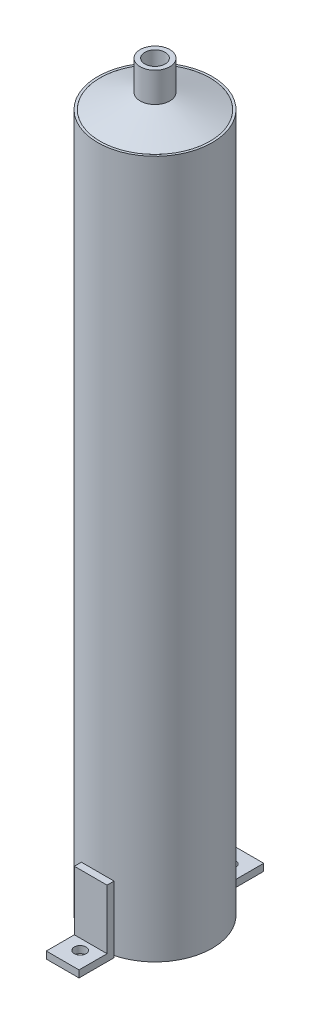
SolidWorks part; units mm, degrees
ref_plane "Front Plane" through (0, 0, 0) normal (0, 0, 1) x (1, 0, 0)
ref_plane "Top Plane" through (0, 0, 0) normal (0, 1, 0) x (1, 0, 0)
ref_plane "Right Plane" through (0, 0, 0) normal (1, 0, 0) x (0, 0, -1)
sketch "Sketch1" plane through (0, 0, 0) normal (0, 1, 0) x (1, 0, 0)
  circle A0 centre (0, 0) radius 23.5
  dimension "D1" = 47
extrude "Extrude-Thin1" add sketch "Sketch1" along normal blind 298.45 thin
ref_plane "Plane1" through (0, 304.8, 0) normal (0, 1, 0) x (1, 0, 0)
sketch "Sketch7" plane through (0, 0, 0) normal (0, -1, 0) x (1, 0, 0)
  line L0 (-27.2962, 0) -> (21.569, 0) construction
  line L1 (0, -24.5) -> (0, 25.9198) construction
  line L3 (-1.524, -21.214) -> (1.524, -21.214)
  line L4 (-1.524, -21.214) -> (-1.524, -23.5)
  line L5 (-1.524, -23.5) -> (1.524, -23.5)
  line L6 (1.524, -21.214) -> (1.524, -23.5)
  line L7 (-1.524, -21.214) -> (1.524, -23.5) construction
  line L8 (-1.524, -23.5) -> (1.524, -21.214) construction
  line L20 (-21.214, 1.524) -> (-23.5, 1.524)
  line L21 (-21.214, 1.524) -> (-21.214, -1.524)
  line L22 (-21.214, -1.524) -> (-23.5, -1.524)
  line L23 (-23.5, 1.524) -> (-23.5, -1.524)
  line L24 (1.524, 21.214) -> (1.524, 23.5)
  line L25 (1.524, 21.214) -> (-1.524, 21.214)
  line L26 (-1.524, 21.214) -> (-1.524, 23.5)
  line L27 (1.524, 23.5) -> (-1.524, 23.5)
  line L28 (21.214, -1.524) -> (23.5, -1.524)
  line L29 (21.214, -1.524) -> (21.214, 1.524)
  line L30 (21.214, 1.524) -> (23.5, 1.524)
  line L31 (23.5, -1.524) -> (23.5, 1.524)
  circle A1 centre (0, 0) radius 24.5 construction
  point P5 (0, -22.357)
  point P20 (-0.95, 0.95)
  point P22 (0.3388, -0.1438)
  point P29 (0.5, -0.5)
  point P30 (0, 0)
  dimension "D1" = 2.286
  dimension "D2" = 3.048
  dimension "D4" = 2.143
  dimension "D3" = 1.524
  dimension "D5" = 4
extrude "Boss-Extrude1" add sketch "Sketch7" against normal blind 261.62 separate body
sketch "Sketch9" plane through (0, 298.45, 0) normal (0, 1, 0) x (1, 0, 0)
  circle A2 centre (0, 0) radius 23.5
sketch "Sketch10" plane through (0, 304.8, 0) normal (0, 1, 0) x (1, 0, 0)
  circle A0 centre (0, 0) radius 6.35
loft "Loft1" add profiles "Sketch10", "Sketch9"
sketch "Sketch11" plane through (0, 304.8, 0) normal (0, 1, 0) x (1, 0, 0)
  circle A0 centre (0, 0) radius 6.35
extrude "Extrude-Thin2" add sketch "Sketch11" along normal blind 12.7 thin thin type one direction reverse wall 2
sketch "Sketch12" plane through (0, 0, 0) normal (0, -1, 0) x (1, 0, 0)
  line L0 (0, 40.0617) -> (0, -14.6613) construction
  line L1 (-7, 39.5) -> (7, 39.5)
  line L2 (-7, 39.5) -> (-7, 24.5)
  line L3 (-7, 24.5) -> (7, 24.5)
  line L4 (7, 39.5) -> (7, 24.5)
  line L5 (27.8316, 0) -> (-29.9513, 0) construction
  line L6 (-7, -24.5) -> (7, -24.5)
  line L7 (7, -39.5) -> (7, -24.5)
  line L8 (-7, -39.5) -> (7, -39.5)
  line L9 (-7, -39.5) -> (-7, -24.5)
  circle A0 centre (0, 0) radius 24.5 construction
  dimension "D1" = 7
  dimension "D2" = 14
  dimension "D3" = 15
extrude "Boss-Extrude2" add sketch "Sketch12" against normal blind 3 separate body
sketch "Sketch13" plane through (0, 3, 0) normal (0, 1, 0) x (1, 0, 0)
  line L0 (-7, -39.5) -> (-7, -24.5) construction
  line L1 (7, -24.5) -> (-7, -24.5)
  line L2 (7, -24.5) -> (7, -27.5)
  line L3 (7, -27.5) -> (-7, -27.5)
  line L4 (-7, -24.5) -> (-7, -27.5)
  line L5 (31.8349, 0) -> (-29.3153, 0) construction
  line L6 (-7, 24.5) -> (-7, 27.5)
  line L7 (7, 24.5) -> (-7, 24.5)
  line L8 (7, 24.5) -> (7, 27.5)
  line L9 (7, 27.5) -> (-7, 27.5)
  dimension "D1" = 3
extrude "Boss-Extrude3" add sketch "Sketch13" along normal blind 25.4
sketch "Sketch14" plane through (0, 3, 0) normal (0, 1, 0) x (1, 0, 0)
  line L0 (7, -39.5) -> (-7, -39.5) construction
  line L1 (7, -24.5) -> (7, -39.5) construction
  line L2 (31.6411, 0) -> (-33.3855, 0) construction
  circle A0 centre (0, -32) radius 2.5187
  circle A1 centre (0, 32) radius 2.5187
  point P4 (0, -39.5)
  dimension "D1" = 7.5
  dimension "D2" = 7
extrude "Cut-Extrude2" cut sketch "Sketch14" against normal up to surface (3 mm away) up to face at (0, 0, -32)
